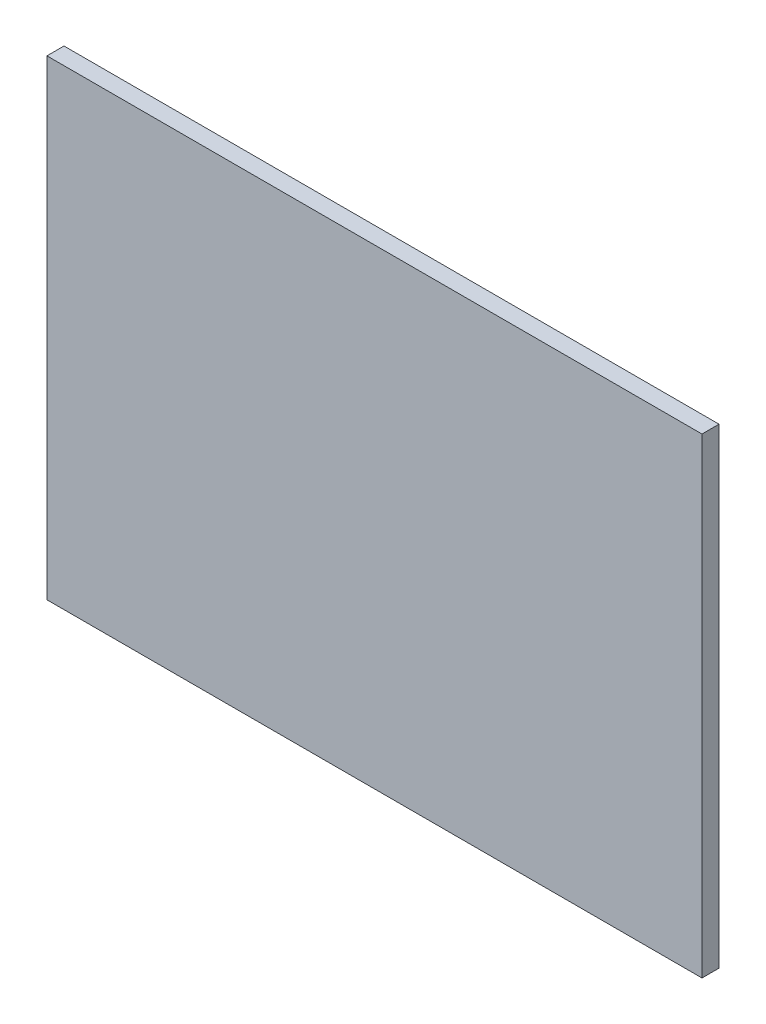
SolidWorks part; units mm, degrees
ref_plane "Front" through (0, 0, 0) normal (0, 0, 1) x (1, 0, 0)
ref_plane "Top" through (0, 0, 0) normal (0, 1, 0) x (1, 0, 0)
ref_plane "Right" through (0, 0, 0) normal (1, 0, 0) x (0, 0, -1)
sketch "Sketch2" plane through (0, 0, 0) normal (0, 0, 1) x (1, 0, 0)
  line L1 (-52.9649, 71.3918) -> (24.3751, 71.3918)
  line L2 (-52.9649, 71.3918) -> (-52.9649, -15.9782)
  line L3 (-52.9649, -15.9782) -> (24.3751, -15.9782)
  line L4 (24.3751, 71.3918) -> (24.3751, -15.9782)
extrude "Boss-Extrude1" add sketch "Sketch2" along normal blind 3.16
sketch "草图1" plane through (-52.9649, 0, 0) normal (-1, 0, 0) x (0, 0, 1)
  line L1 (3.16, 71.3918) -> (0, 71.3918)
  line L2 (3.16, 71.3918) -> (3.16, -15.9782)
  line L3 (3.16, -15.9782) -> (0, -15.9782)
  line L4 (0, 71.3918) -> (0, -15.9782)
sketch "草图3" plane through (24.3751, 0, 0) normal (1, 0, 0) x (0, 0, -1)
  line L1 (-3.16, 71.3918) -> (0, 71.3918)
  line L2 (-3.16, 71.3918) -> (-3.16, -15.9782)
  line L3 (-3.16, -15.9782) -> (0, -15.9782)
  line L4 (0, 71.3918) -> (0, -15.9782)
extrude "凸台-拉伸3" add sketch "草图3" along normal blind 80
sketch "草图4" plane through (-52.9649, 0, 0) normal (-1, 0, 0) x (0, 0, 1)
  line L1 (3.16, 71.3918) -> (0, 71.3918)
  line L2 (3.16, 71.3918) -> (3.16, -15.9782)
  line L3 (3.16, -15.9782) -> (0, -15.9782)
  line L4 (0, 71.3918) -> (0, -15.9782)
extrude "凸台-拉伸4" add sketch "草图4" along normal blind 60
sketch "草图5" plane through (104.3751, 0, 0) normal (1, 0, 0) x (0, 0, -1)
  line L0 (0, 71.3918) -> (-3.16, 71.3918) construction
  line L1 (-3.16, 71.3918) -> (0, 71.3918)
  line L2 (-3.16, 71.3918) -> (-3.16, -15.9782)
  line L3 (-3.16, -15.9782) -> (0, -15.9782)
  line L4 (0, 71.3918) -> (0, -15.9782)
  line L5 (-3.16, 71.3918) -> (-3.16, -15.9782) construction
extrude "凸台-拉伸5" add sketch "草图5" along normal blind 113
sketch "草图6" plane through (217.3751, 0, 0) normal (1, 0, 0) x (0, 0, -1)
  line L0 (-3.16, -15.9782) -> (0, -15.9782) construction
  line L1 (-3.16, 71.3918) -> (0, 71.3918)
  line L2 (-3.16, 71.3918) -> (-3.16, -15.9782)
  line L3 (-3.16, -15.9782) -> (0, -15.9782)
  line L4 (0, 71.3918) -> (0, -15.9782)
  line L5 (0, -15.9782) -> (0, 71.3918) construction
extrude "切除-拉伸1" cut sketch "草图6" against normal blind 17.86 contours L4 L3 L2 L1
sketch "草图8" plane through (0, 0, 3.16) normal (0, 0, 1) x (1, 0, 0)
  circle A0 centre (175.7936, 23.4753) radius 12.75
extrude "切除-拉伸2" cut sketch "草图8" against normal blind 10
sketch "草图9" plane through (199.5151, 0, 0) normal (1, 0, 0) x (0, 0, -1)
  line L1 (-3.16, 71.3918) -> (0, 71.3918)
  line L2 (-3.16, 71.3918) -> (-3.16, -15.9782)
  line L3 (-3.16, -15.9782) -> (0, -15.9782)
  line L4 (0, 71.3918) -> (0, -15.9782)
extrude "切除-拉伸3" cut sketch "草图9" against normal blind 171
sketch "草图10" plane through (-112.9649, 0, 0) normal (-1, 0, 0) x (0, 0, 1)
  line L0 (3.16, -15.9782) -> (3.16, 71.3918) construction
  line L1 (0, 71.3918) -> (3.16, 71.3918)
  line L2 (0, 71.3918) -> (0, -15.9782)
  line L3 (0, -15.9782) -> (3.16, -15.9782)
  line L4 (3.16, 71.3918) -> (3.16, -15.9782)
extrude "切除-拉伸4" cut sketch "草图10" against normal blind 60
extrude "凸台-拉伸6" add sketch "草图1" along normal blind 20 contours L4 L3 L2 L1
sketch "草图11" plane through (28.5151, 0, 0) normal (1, 0, 0) x (0, 0, -1)
  line L1 (-3.16, 71.3918) -> (0, 71.3918)
  line L2 (-3.16, 71.3918) -> (-3.16, -15.9782)
  line L3 (-3.16, -15.9782) -> (0, -15.9782)
  line L4 (0, 71.3918) -> (0, -15.9782)
extrude "凸台-拉伸7" add sketch "草图11" along normal blind 20
